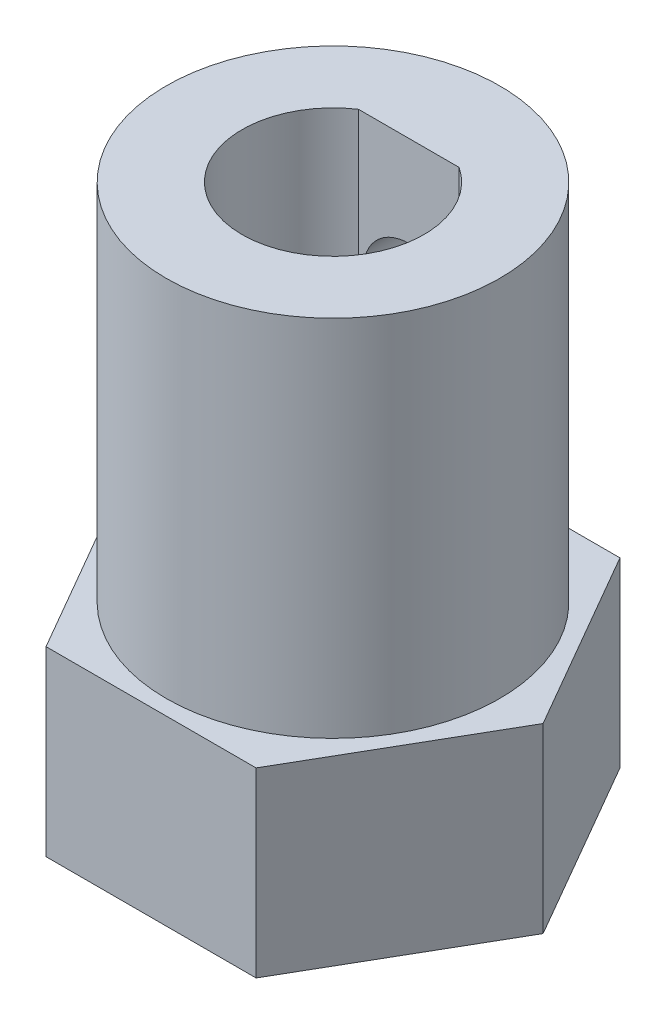
SolidWorks part; units mm, degrees
ref_plane "Alzado" through (0, 0, 0) normal (0, 0, 1) x (1, 0, 0)
ref_plane "Planta" through (0, 0, 0) normal (0, 1, 0) x (1, 0, 0)
ref_plane "Vista lateral" through (0, 0, 0) normal (1, 0, 0) x (0, 0, -1)
sketch "Croquis hex-head" plane through (0, 0, 0) normal (0, 1, 0) x (1, 0, 0)
  line L1 (6.9282, 0) -> (3.4641, 6)
  line L2 (3.4641, 6) -> (-3.4641, 6)
  line L3 (-3.4641, 6) -> (-6.9282, 0)
  line L4 (-6.9282, 0) -> (-3.4641, -6)
  line L5 (-3.4641, -6) -> (3.4641, -6)
  line L6 (3.4641, -6) -> (6.9282, 0)
  circle A0 centre (0, 0) radius 6 construction
  dimension "D1" = 12
extrude "Saliente-Extruir1" add sketch "Croquis hex-head" along normal blind 6
sketch "Croquis body" plane through (0, 6, 0) normal (0, 1, 0) x (1, 0, 0)
  circle A0 centre (0, 0) radius 5.5
  dimension "D1" = 11
extrude "Saliente-Extruir2" add sketch "Croquis body" along normal blind 12
sketch "Croquis inner" plane through (0, 18, 0) normal (0, 1, 0) x (1, 0, 0)
  line L0 (0, 3) -> (0, -3) construction
  line L1 (-1.6583, 2.5) -> (1.6583, 2.5)
  arc A0 (-1.6583, 2.5) -> (1.6583, 2.5) centre (0, 0) ccw
  dimension "D1" = 6
  dimension "D2" = 5.5
extrude "Cortar-Extruir1" cut sketch "Croquis inner" against normal blind 12
sketch "Croquis5" plane through (0, 0, -6) normal (0, 0, -1) x (-1, 0, 0)
  line L0 (0, 0) -> (0, 18) construction
  line L1 (5.5, 18) -> (-5.5, 18) construction
  circle A0 centre (0, 13.5) radius 1.5
  dimension "D1" = 3
  dimension "D2" = 4.5
extrude "Cortar-Extruir2" cut sketch "Croquis5" against normal up to surface (3.5 mm away) up to face at (0, 12, -2.5)
sketch "Croquis6" plane through (0, 0, 0) normal (0, -1, 0) x (1, 0, 0)
  circle A0 centre (0, 0) radius 2
  dimension "D1" = 4
extrude "Cortar-Extruir3" cut sketch "Croquis6" against normal up to surface (6 mm away) up to face at (0, 6, 0.25)
